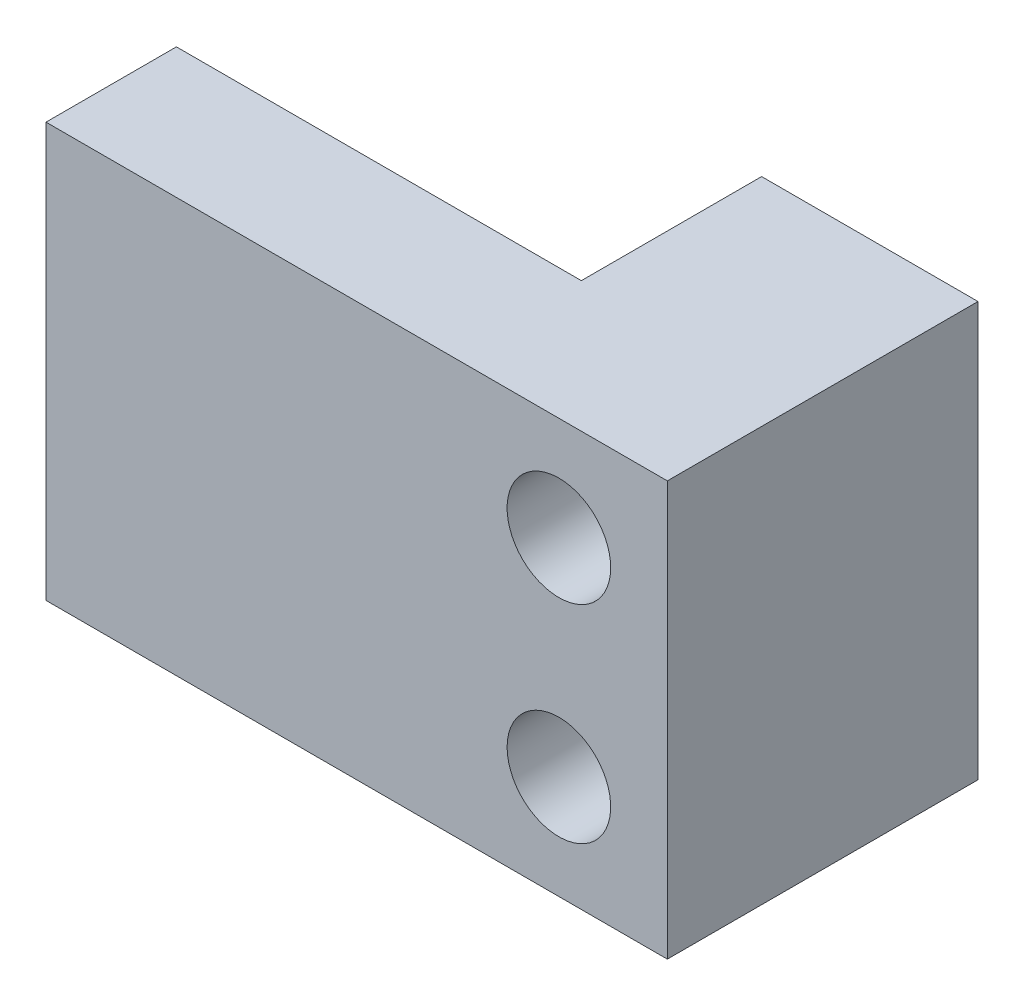
SolidWorks part; units mm, degrees
ref_plane "Plan de face" through (0, 0, 0) normal (0, 0, 1) x (1, 0, 0)
ref_plane "Plan de dessus" through (0, 0, 0) normal (0, 1, 0) x (1, 0, 0)
ref_plane "Plan de droite" through (0, 0, 0) normal (1, 0, 0) x (0, 0, -1)
sketch "Esquisse1" plane through (0, 0, 0) normal (0, 0, 1) x (1, 0, 0)
  line L0 (0, 10) -> (0, -10) construction
  line L1 (-15, -10) -> (15, -10)
  line L2 (-15, -10) -> (-15, 10)
  line L3 (-15, 10) -> (15, 10)
  line L4 (15, -10) -> (15, 10)
  line L5 (-15, -10) -> (15, 10) construction
  line L6 (-15, 10) -> (15, -10) construction
  line L7 (0, 0) -> (7.09, 0) construction
  circle A0 centre (9.7638, 5) radius 2.5
  circle A1 centre (9.7638, -5) radius 2.5
  point P0 (0, 0)
  dimension "D3" = 5
  dimension "D1" = 30
  dimension "D2" = 20
  dimension "D4" = 5
extrude "Boss.-Extru.1" add sketch "Esquisse1" along normal blind 15
sketch "Esquisse2" plane through (0, 10, 0) normal (0, 1, 0) x (1, 0, 0)
  line L1 (-15, 0) -> (4.5521, 0)
  line L2 (-15, 0) -> (-15, -8.7033)
  line L3 (-15, -8.7033) -> (4.5521, -8.7033)
  line L4 (4.5521, 0) -> (4.5521, -8.7033)
extrude "Enlèv. mat.-Extru.1" cut sketch "Esquisse2" against normal blind 11
